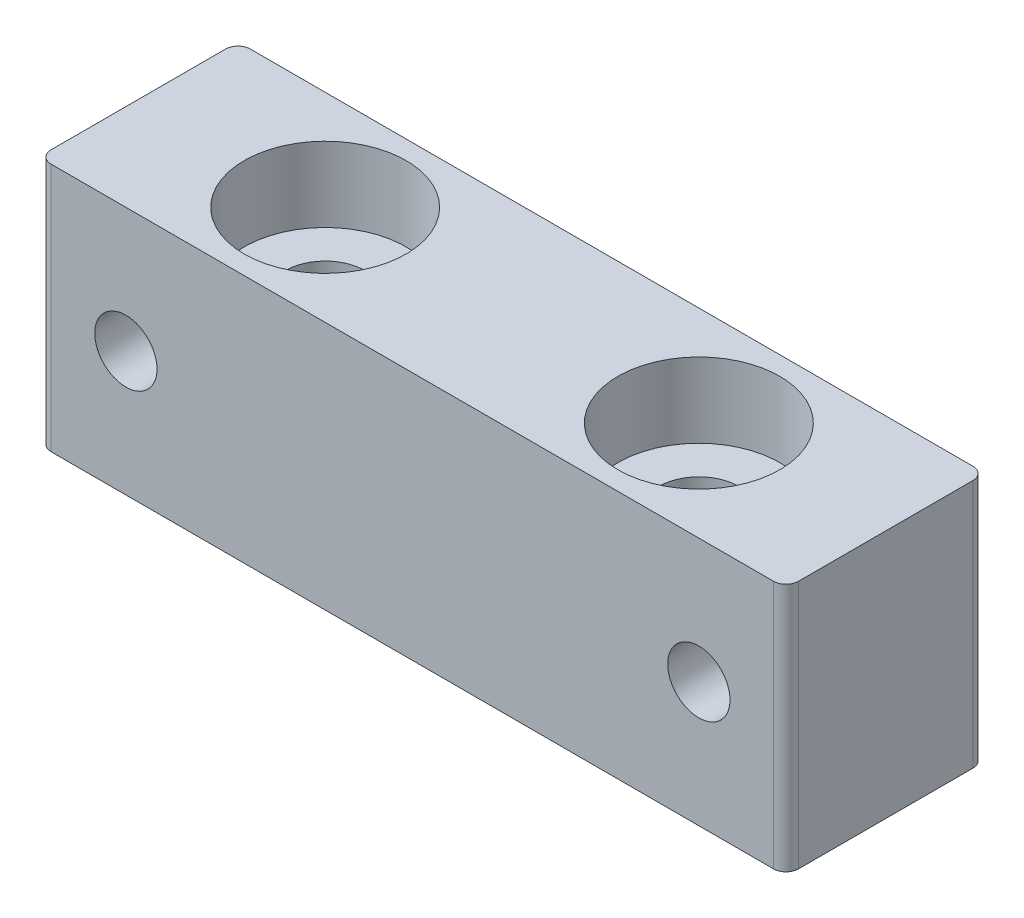
SolidWorks part; units mm, degrees
material "AISI 1045 Steel, cold drawn"
ref_plane "Front Plane" through (0, 0, 0) normal (0, 0, 1) x (1, 0, 0)
ref_plane "Top Plane" through (0, 0, 0) normal (0, 1, 0) x (1, 0, 0)
ref_plane "Right Plane" through (0, 0, 0) normal (1, 0, 0) x (0, 0, -1)
sketch "Sketch1" plane through (0, 0, 0) normal (0, 1, 0) x (1, 0, 0)
  line L1 (15, -4) -> (-15, -4)
  line L2 (15, -4) -> (15, 4)
  line L3 (15, 4) -> (-15, 4)
  line L4 (-15, -4) -> (-15, 4)
  line L5 (15, -4) -> (-15, 4) construction
  line L6 (15, 4) -> (-15, -4) construction
  point P0 (0, 0)
  dimension "D1" = 8
  dimension "D2" = 30
extrude "Boss-Extrude1" add sketch "Sketch1" along normal blind 10
hole_wizard "CBORE for M3 SHCS2" positions "Sketch2" profile "Sketch4" counterbore size "M3" standard "ANSI Metric" end condition through all
sketch "Sketch2" plane through (0, 10, 0) normal (0, 1, 0) x (1, 0, 0)
  line L0 (-7.5, 0) -> (7.5, 0) construction
  point P0 (-7.5, 0)
  point P2 (7.5, 0)
  point P8 (0, 0)
  dimension "D1" = 15
sketch "Sketch4" plane through (-7.5, 10, 0) normal (1, 0, 0) x (0, 0, 1)
  line L0 (0, 0) -> (0, 10)
  line L1 (0, 10) -> (1.6, 10)
  line L3 (1.6, 10) -> (1.6, 3)
  line L4 (1.6, 3) -> (3.25, 3)
  line L5 (3.25, 3) -> (3.25, 0)
  line L7 (3.25, 0) -> (0, 0)
  line L11 (0, -6.35) -> (0, 107.95) construction
  dimension "Thru Hole Dia." = 3.2
  dimension "Thru Hole Depth" = 10
  dimension "C'Bore Dia." = 6.5
  dimension "C'Bore Depth" = 3
hole_wizard "Tap Drill for M3x0.5 Tap1" positions "Sketch5" profile "Sketch7" hole size "M3x0.5" standard "ANSI Metric" end condition through all
sketch "Sketch5" plane through (0, 0, 4) normal (0, 0, 1) x (1, 0, 0)
  line L0 (-11.5, 5) -> (11.5, 5) construction
  line L2 (15, 10) -> (15, 0) construction
  point P0 (-11.5, 5)
  point P2 (11.5, 5)
  point P11 (15, 5)
  point P12 (0, 5)
  dimension "D1" = 23
sketch "Sketch7" plane through (-11.5, 5, 4) normal (1, 0, 0) x (0, -1, 0)
  line L0 (0, 0) -> (0, 8)
  line L1 (0, 8) -> (1.25, 8)
  line L2 (1.25, 8) -> (1.25, 0)
  line L5 (1.25, 0) -> (0, 0)
  line L11 (0, -6.35) -> (0, 107.95) construction
  dimension "Thru Hole Dia." = 2.5
  dimension "Thru Hole Depth" = 8
fillet "Fillet1" radius 0.5 4 edges at (15, 5, 4) (15, 5, -4) (-15, 5, 4) (-15, 5, -4)
